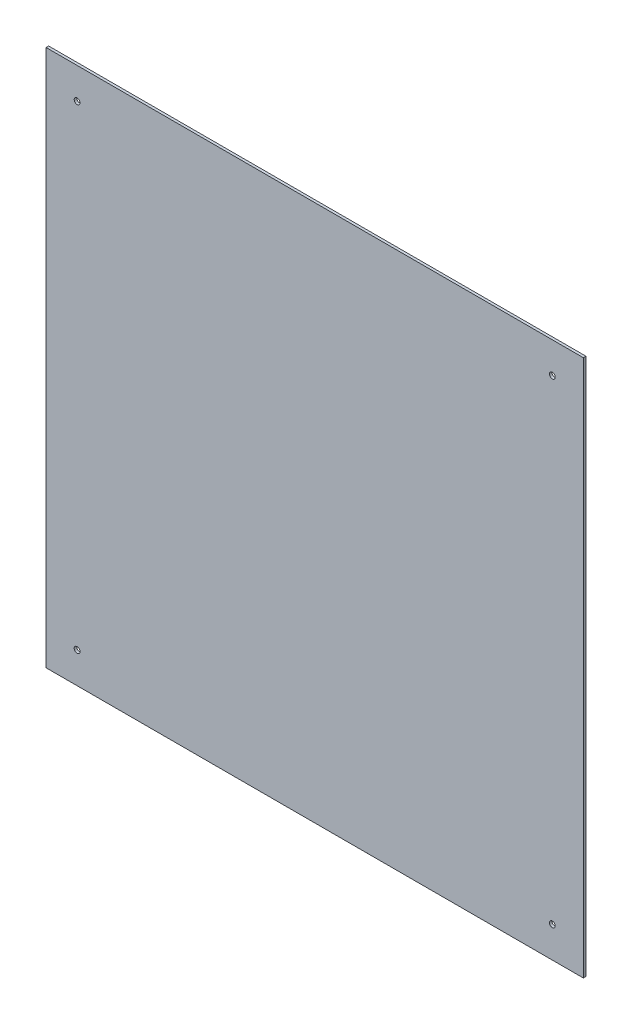
SolidWorks part; units mm, degrees
ref_plane "Front Plane" through (0, 0, 0) normal (0, 0, 1) x (1, 0, 0)
ref_plane "Top Plane" through (0, 0, 0) normal (0, 1, 0) x (1, 0, 0)
ref_plane "Right Plane" through (0, 0, 0) normal (1, 0, 0) x (0, 0, -1)
sketch "Sketch1" plane through (0, 0, 0) normal (0, 0, 1) x (1, 0, 0)
  line L0 (0, 330.2) -> (660.4, 330.2) construction
  line L1 (0, 0) -> (660.4, 0)
  line L2 (0, 0) -> (0, 660.4)
  line L3 (0, 660.4) -> (660.4, 660.4)
  line L4 (660.4, 0) -> (660.4, 660.4)
  line L5 (660.4, 330.2) -> (330.2, 660.4) construction
  line L6 (330.2, 660.4) -> (330.2, 0) construction
  line L7 (330.2, 479.679) -> (330.2, 180.721) construction
  line L8 (38.1, 622.3) -> (38.1, 660.4) construction
  line L9 (38.1, 622.3) -> (0, 622.3) construction
  circle A0 centre (330.2, 479.679) radius 2.5 construction
  circle A1 centre (330.2, 180.721) radius 2.5 construction
  circle A2 centre (38.1, 622.3) radius 3.556
  circle A3 centre (622.3, 622.3) radius 3.556
  circle A4 centre (622.3, 38.1) radius 3.556
  circle A5 centre (38.1, 38.1) radius 3.556
  point P12 (330.2, 330.2)
  dimension "D1" = 5
  dimension "D7" = 7.112
  dimension "D2" = 660.4
  dimension "D3" = 660.4
  dimension "D4" = 298.958
  dimension "D5" = 180.721
  dimension "D6" = 180.721
  dimension "D8" = 38.1
  dimension "D9" = 38.1
  dimension "D10" = 38.1
  dimension "D11" = 38.1
  dimension "D12" = 38.1
  dimension "D13" = 38.1
  dimension "D14" = 38.1
  dimension "D15" = 38.1
extrude "Boss-Extrude1" add sketch "Sketch1" along normal blind 3.175
